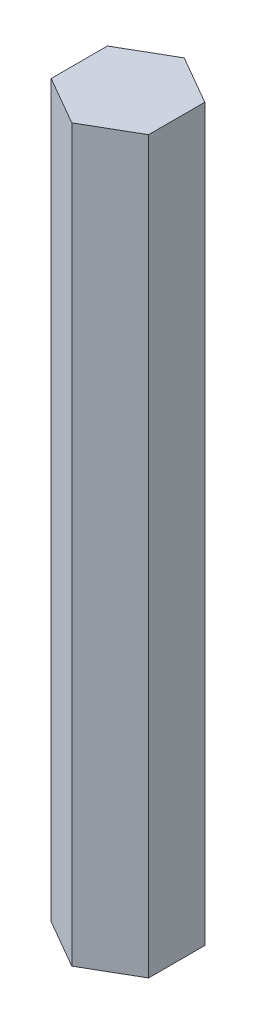
SolidWorks part; units mm, degrees
ref_plane "정면" through (0, 0, 0) normal (0, 0, 1) x (1, 0, 0)
ref_plane "윗면" through (0, 0, 0) normal (0, 1, 0) x (1, 0, 0)
ref_plane "우측면" through (0, 0, 0) normal (1, 0, 0) x (0, 0, -1)
sketch "스케치1" plane through (0, 0, 0) normal (0, 1, 0) x (1, 0, 0)
  line L1 (0, -3.4641) -> (3, -1.7321)
  line L2 (3, -1.7321) -> (3, 1.7321)
  line L3 (3, 1.7321) -> (0, 3.4641)
  line L4 (0, 3.4641) -> (-3, 1.7321)
  line L5 (-3, 1.7321) -> (-3, -1.7321)
  line L6 (-3, -1.7321) -> (0, -3.4641)
  circle A0 centre (0, 0) radius 3 construction
extrude "보스-돌출1" add sketch "스케치1" along normal blind 45
